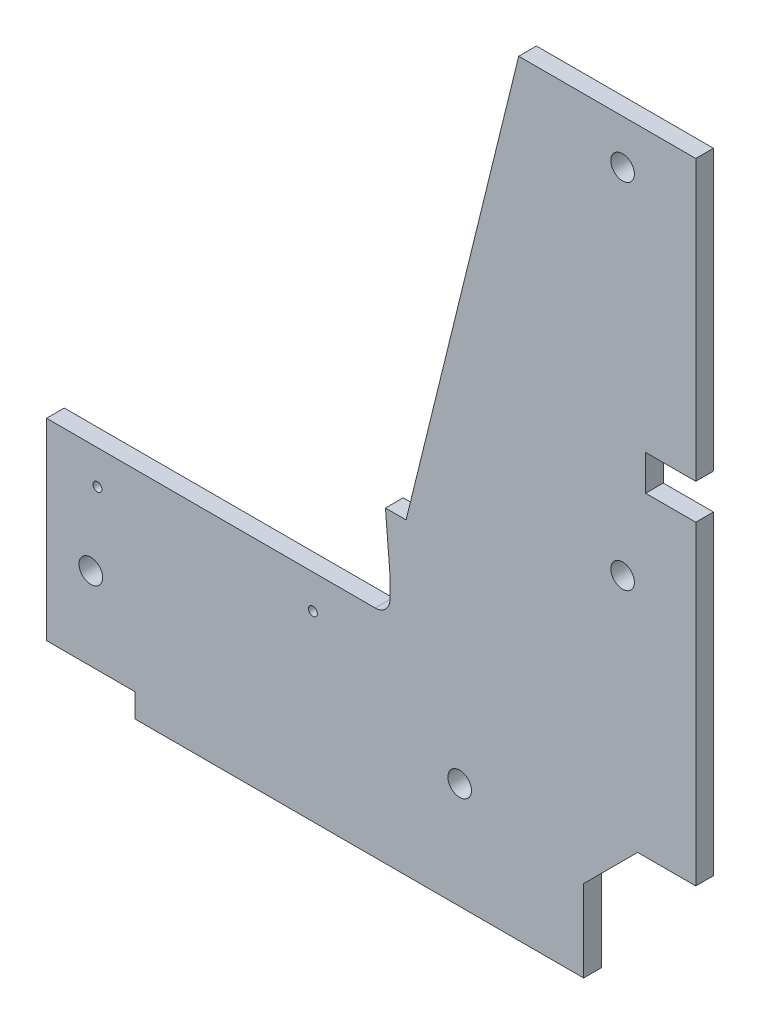
SolidWorks part; units mm, degrees
ref_plane "Front Plane" through (0, 0, 0) normal (0, 0, 1) x (1, 0, 0)
ref_plane "Top Plane" through (0, 0, 0) normal (0, 1, 0) x (1, 0, 0)
ref_plane "Right Plane" through (0, 0, 0) normal (1, 0, 0) x (0, 0, -1)
sketch "Sketch1" plane through (0, 0, 0) normal (0, 0, 1) x (1, 0, 0)
  line L0 (0, 0) -> (-220, 0)
  line L1 (-220, 0) -> (-220, 71.45)
  line L3 (-60, 259.8) -> (0, 259.8)
  line L4 (0, 259.8) -> (0, 0)
  line L5 (-140, 71.45) -> (-140, 58.45) construction
  line L6 (-210, 71.45) -> (-140, 71.45) construction
  line L7 (-210, 71.45) -> (-210, 27.79) construction
  line L8 (-210, 27.79) -> (-110, 27.79) construction
  line L9 (-110, 58.45) -> (-110, 27.79) construction
  line L10 (-140, 58.45) -> (-110, 58.45) construction
  line L11 (-220, 71.45) -> (-116.3894, 71.45)
  line L12 (-101.8943, 82.9131) -> (-60, 259.8)
  arc A5 (-116.3894, 71.45) -> (-101.8943, 82.9131) centre (-116.3894, 86.3461) ccw
  dimension "D1" = 259.8
  dimension "D2" = 220
  dimension "D3" = 71.45
  dimension "D4" = 43.66
  dimension "D5" = 100
  dimension "D6" = 27.79
  dimension "D7" = 10
  dimension "D8" = 70
  dimension "D9" = 13
  dimension "D10" = 71.45
  dimension "D11" = 14.4951
  dimension "D12" = 60
  dimension "D15" = 11.4631
extrude "Boss-Extrude2" add sketch "Sketch1" along normal blind 6
sketch "Sketch2" plane through (0, 0, 6) normal (0, 0, 1) x (1, 0, 0)
  line L0 (-220, 0) -> (0, 0) construction
  line L1 (-220, 0) -> (-190, 0)
  line L2 (-220, 0) -> (-220, 8.3)
  line L3 (-220, 8.3) -> (-190, 8.3)
  line L4 (-190, 0) -> (-190, 8.3)
  line L5 (-38, 0) -> (-38, 19)
  line L6 (-220, 71.45) -> (-220, 0) construction
  line L7 (-190, 46.3) -> (-220, 46.3) construction
  line L8 (-190, 8.3) -> (-190, 46.3) construction
  line L11 (-10.7, 46.3) -> (0, 46.3)
  line L12 (0, 0) -> (0, 259.8) construction
  line L20 (-38, 0) -> (0, 0)
  line L21 (0, 0) -> (0, 259.8) construction
  line L24 (0, 259.8) -> (-60, 259.8) construction
  line L25 (-9.8, 259.8) -> (-9.8, 0) construction
  line L26 (-190, 8.3) -> (0, 8.3) construction
  line L28 (0, 0) -> (0, 46.3)
  line L29 (-38, 19) -> (-10.7, 46.3)
  circle A0 centre (-205, 36.3) radius 4
  circle A2 centre (-24.8, 244.8) radius 4
  circle A3 centre (-24.8, 125) radius 4
  circle A4 centre (-80, 43.8) radius 4
  dimension "D3" = 8
  dimension "D6" = 15
  dimension "D1" = 8.3
  dimension "D2" = 30
  dimension "D4" = 28
  dimension "D5" = 15
  dimension "D7" = 38
  dimension "D8" = 45
  dimension "D9" = 19
  dimension "D10" = 38
  dimension "D11" = 46.3
  dimension "D15" = 43.8
  dimension "D16" = 80
  dimension "D17" = 24.8
  dimension "D18" = 9.8
  dimension "D21" = 125
extrude "Cut-Extrude1" cut sketch "Sketch2" against normal through all
sketch "Croquis1" plane through (0, 0, 6) normal (0, 0, 1) x (1, 0, 0)
  line L1 (-220, 71.45) -> (-116.3894, 71.45)
  line L2 (-220, 71.45) -> (-220, 73.01)
  line L3 (-220, 73.01) -> (-116.3894, 73.01)
  line L4 (-116.3894, 71.45) -> (-116.3894, 73.01)
extrude "Saliente-Extruir2" add sketch "Croquis1" against normal blind 6
sketch "Croquis3" plane through (0, 0, 6) normal (0, 0, 1) x (1, 0, 0)
  line L0 (-116.3894, 86.3461) -> (-101.8943, 82.9131) construction
  line L1 (-101.8943, 82.9131) -> (-103.4123, 83.2726)
  line L2 (-103.4123, 83.2726) -> (-60, 259.8)
  line L3 (-60, 259.8) -> (-101.8943, 82.9131)
extrude "Saliente-Extruir3" add sketch "Croquis3" against normal blind 6
sketch "Croquis4" plane through (0, 0, 6) normal (0, 0, 1) x (1, 0, 0)
  line L0 (-116.3894, 71.45) -> (-116.3894, 73.01) construction
  line L1 (-103.4123, 83.2726) -> (-101.8943, 82.9131)
  line L2 (-116.3894, 73.01) -> (-116.3894, 71.45)
  arc A0 (-101.8943, 82.9131) -> (-116.3894, 71.45) centre (-116.3894, 86.3461) cw
  arc A1 (-103.4123, 83.2726) -> (-116.3894, 73.01) centre (-116.3894, 86.3461) cw
extrude "Saliente-Extruir4" add sketch "Croquis4" against normal blind 6
sketch "Croquis5" plane through (0, 0, 6) normal (0, 0, 1) x (1, 0, 0)
  line L0 (-105, 102.74) -> (-55, 102.74)
  line L1 (-190, 8.3) -> (-220, 8.3) construction
  line L2 (-220, 73.01) -> (-220, 8.3) construction
  line L3 (-105, 102.74) -> (-103.4123, 83.2726)
  line L4 (-103.4123, 83.2726) -> (-55, 102.74)
  dimension "D1" = 94.44
  dimension "D2" = 115
  dimension "D3" = 50
extrude "Saliente-Extruir5" add sketch "Croquis5" against normal blind 6
sketch "Croquis6" plane through (0, 0, 6) normal (0, 0, 1) x (1, 0, 0)
  line L0 (-98.1575, 104.64) -> (-105.155, 104.64)
  line L1 (-60, 259.8) -> (-98.6248, 102.74) construction
  line L2 (-190, 8.3) -> (-220, 8.3) construction
  line L3 (-105, 102.74) -> (-105.155, 104.64)
  line L4 (-105, 102.74) -> (-103.4123, 83.2726) construction
  line L5 (-98.1575, 104.64) -> (-98.6248, 102.74)
  line L6 (-98.6248, 102.74) -> (-105, 102.74)
  point P6 (-101.6562, 104.64)
  dimension "D1" = 96.34
  dimension "D2" = 180
extrude "Saliente-Extruir6" add sketch "Croquis6" against normal blind 6
sketch "Croquis7" plane through (0, 0, 6) normal (0, 0, 1) x (1, 0, 0)
  line L0 (-220, 73.01) -> (-220, 73.57)
  line L1 (-220, 73.57) -> (-116.3894, 73.57)
  line L2 (-116.3894, 73.57) -> (-116.3894, 73.01)
  line L3 (-116.3894, 73.01) -> (-220, 73.01)
  dimension "D1" = 65.27
  dimension "D2" = 90
extrude "Saliente-Extruir7" add sketch "Croquis7" against normal blind 6
sketch "Croquis8" plane through (0, 0, 6) normal (0, 0, 1) x (1, 0, 0)
  line L0 (-105.155, 104.64) -> (-103.4123, 83.2726) construction
  line L1 (-116.3894, 73.57) -> (-117.9888, 71.6527)
  line L2 (-117.9888, 71.6527) -> (-105.3806, 73.0577)
  line L3 (-105.3806, 73.0577) -> (-100.6848, 83.3735)
  line L4 (-100.6848, 83.3735) -> (-103.6228, 85.8535)
  arc A0 (-116.3894, 73.57) -> (-103.6228, 85.8535) centre (-116.3894, 86.3461) ccw
extrude "Saliente-Extruir8" add sketch "Croquis8" against normal blind 6
sketch "Sketch3" plane through (0, 0, 6) normal (0, 0, 1) x (1, 0, 0)
  line L0 (-116.3894, 73.57) -> (-220, 73.57) construction
  line L1 (-220, 73.57) -> (-220, 8.3) construction
  circle A0 centre (-202.75, 62.07) radius 1.5
  circle A1 centre (-129.75, 62.07) radius 1.5
  dimension "D1" = 3
  dimension "D2" = 3
  dimension "D3" = 11.5
  dimension "D4" = 17.25
  dimension "D5" = 73
extrude "Cut-Extrude2" cut sketch "Sketch3" against normal through all
sketch "Sketch4" plane through (0, 0, 6) normal (0, 0, 1) x (1, 0, 0)
  line L0 (-103.6228, 85.8535) -> (-103.6228, 78.57)
  line L1 (-116.3894, 73.57) -> (-108.6228, 73.57)
  arc A0 (-108.6228, 73.57) -> (-103.6228, 78.57) centre (-108.6228, 78.57) ccw
  arc A1 (-103.6228, 85.8535) -> (-116.3894, 73.57) centre (-116.3894, 86.3461) cw
  dimension "D1" = 5
extrude "Cut-Extrude3" cut sketch "Sketch4" against normal through all
sketch "Croquis9" plane through (0, 0, 6) normal (0, 0, 1) x (1, 0, 0)
  line L0 (-38, 19) -> (-38, 0) construction
  line L1 (-190, 0) -> (-38, 0)
  line L2 (-190, 0) -> (-190, 0.3)
  line L3 (-190, 0.3) -> (-38, 0.3)
  line L4 (-38, 0) -> (-38, 0.3)
extrude "Cortar-Extruir1" cut sketch "Croquis9" against normal blind 10
sketch "Croquis11" plane through (0, 0, 6) normal (0, 0, 1) x (1, 0, 0)
  line L0 (-10.7, 46.3) -> (-19.7, 46.3)
  line L1 (-38, 19) -> (-38, 28)
  line L2 (-38, 28) -> (-19.7, 46.3)
  line L3 (-38, 19) -> (-10.7, 46.3)
extrude "Cortar-Extruir2" cut sketch "Croquis11" against normal blind 6
sketch "Croquis12" plane through (0, 0, 6) normal (0, 0, 1) x (1, 0, 0)
  circle A0 centre (-80, 36.3) radius 4
  circle A1 centre (-80, 43.8) radius 4 construction
  dimension "D1" = 0
extrude "Cortar-Extruir3" cut sketch "Croquis12" against normal blind 6
sketch "Croquis13" plane through (0, 0, 6) normal (0, 0, 1) x (1, 0, 0)
  circle A0 centre (-80, 43.8) radius 4
  circle A1 centre (-80, 36.3) radius 4
  arc M2 (-81.3919, 40.05) -> (-78.6081, 40.05) centre (-80, 43.8) cw
extrude "Saliente-Extruir9" add sketch "Croquis13" against normal blind 6 contours A1 M2
sketch "Croquis14" plane through (0, 0, 6) normal (0, 0, 1) x (1, 0, 0)
  line L0 (0, 46.3) -> (0, 259.8) construction
  line L1 (0, 153.05) -> (-17, 153.05)
  line L2 (0, 153.05) -> (0, 165.05)
  line L3 (0, 165.05) -> (-17, 165.05)
  line L4 (-17, 153.05) -> (-17, 165.05)
  line L5 (-38, 0.3) -> (-190, 0.3) construction
  dimension "D1" = 152.75
  dimension "D2" = 17
  dimension "D3" = 12
extrude "Cortar-Extruir4" cut sketch "Croquis14" against normal blind 10
